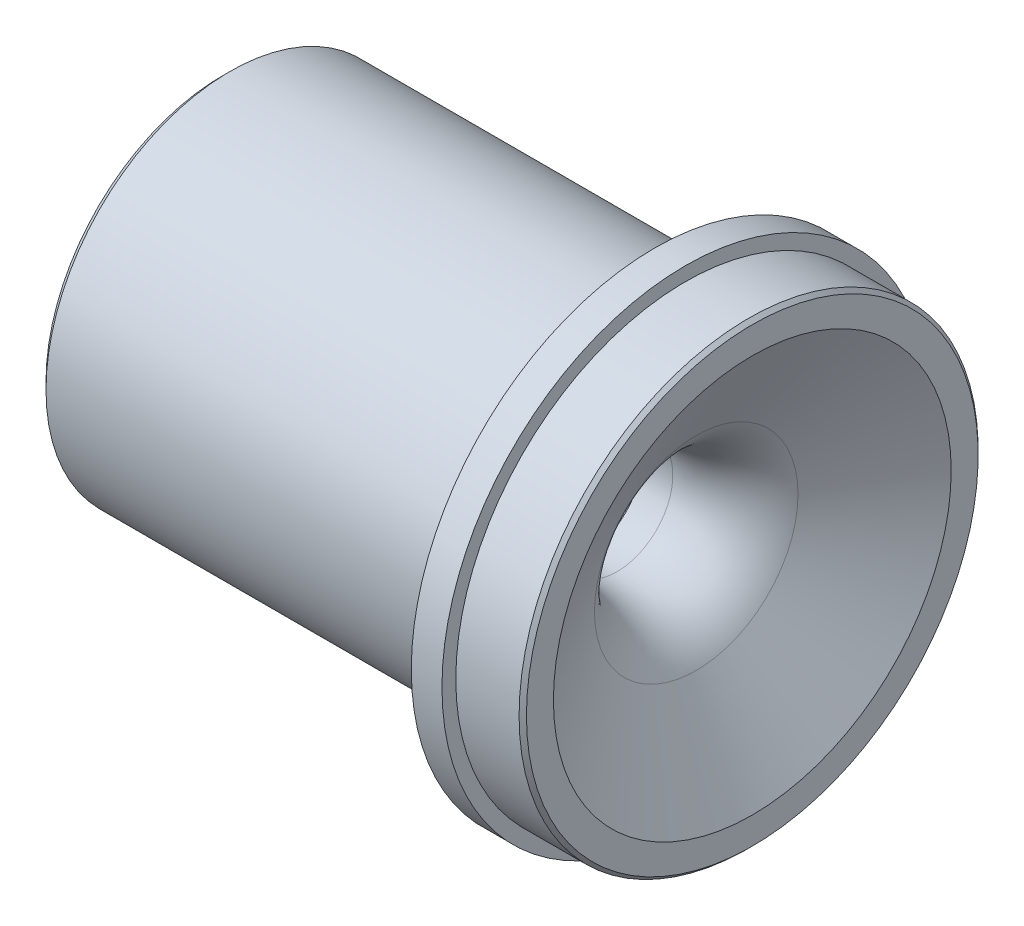
SolidWorks part; units mm, degrees
ref_plane "Front Plane" through (0, 0, 0) normal (0, 0, 1) x (1, 0, 0)
ref_plane "Top Plane" through (0, 0, 0) normal (0, 1, 0) x (1, 0, 0)
ref_plane "Right Plane" through (0, 0, 0) normal (1, 0, 0) x (0, 0, -1)
sketch "Sketch1" plane through (0, 0, 0) normal (0, 0, 1) x (1, 0, 0)
  line L0 (-39.9173, 0) -> (65.9775, 0) construction
  line L1 (-27.432, 15.875) -> (10.2487, 5.7785)
  line L3 (-27.432, 15.875) -> (-27.432, 18.288)
  line L4 (-26.67, 19.05) -> (14.1478, 19.05)
  line L5 (14.1478, 19.05) -> (15.5448, 20.447)
  line L8 (17.3228, 22.2123) -> (17.3228, 25.2095)
  line L9 (17.3228, 25.2095) -> (20.4978, 25.2095)
  line L10 (20.4978, 25.2095) -> (20.4978, 23.7744)
  line L11 (20.4978, 23.7744) -> (27.051, 23.7744)
  line L12 (27.432, 23.3934) -> (27.432, 20.5994)
  line L14 (15.5448, 20.447) -> (15.5448, 22.2123)
  line L15 (15.5448, 22.2123) -> (17.3228, 22.2123)
  line L16 (27.432, 20.5994) -> (21.6247, 10.5409)
  line L17 (0, -37.1392) -> (0, 60.2273) construction
  line L18 (10.2487, 5.7785) -> (13.4237, 5.7785)
  line L19 (-27.432, 18.288) -> (-26.67, 19.05)
  line L20 (27.051, 23.7744) -> (27.432, 23.3934)
  arc A0 (13.4237, 5.7785) -> (21.6247, 10.5409) centre (13.3758, 15.3034) ccw
  point P7 (-27.432, 19.05)
  point P15 (27.432, 23.7744)
  dimension "D16" = 3.175
  dimension "D18" = 9.525
  dimension "D2" = 11.557
  dimension "D3" = 31.75
  dimension "D4" = 54.864
  dimension "D5" = 41.1988
  dimension "D6" = 15
  dimension "D7" = 6.9342
  dimension "D8" = 10.1092
  dimension "D9" = 11.8872
  dimension "D10" = 13.2842
  dimension "D11" = 38.1
  dimension "D12" = 47.5488
  dimension "D13" = 50.419
  dimension "D14" = 44.4246
  dimension "D15" = 40.894
  dimension "D17" = 60
  dimension "D19" = 0.762
  dimension "D20" = 45
  dimension "D21" = 0.381
  dimension "D22" = 45
revolve "Revolve1" add sketch "Sketch1" angle 360 about L0
